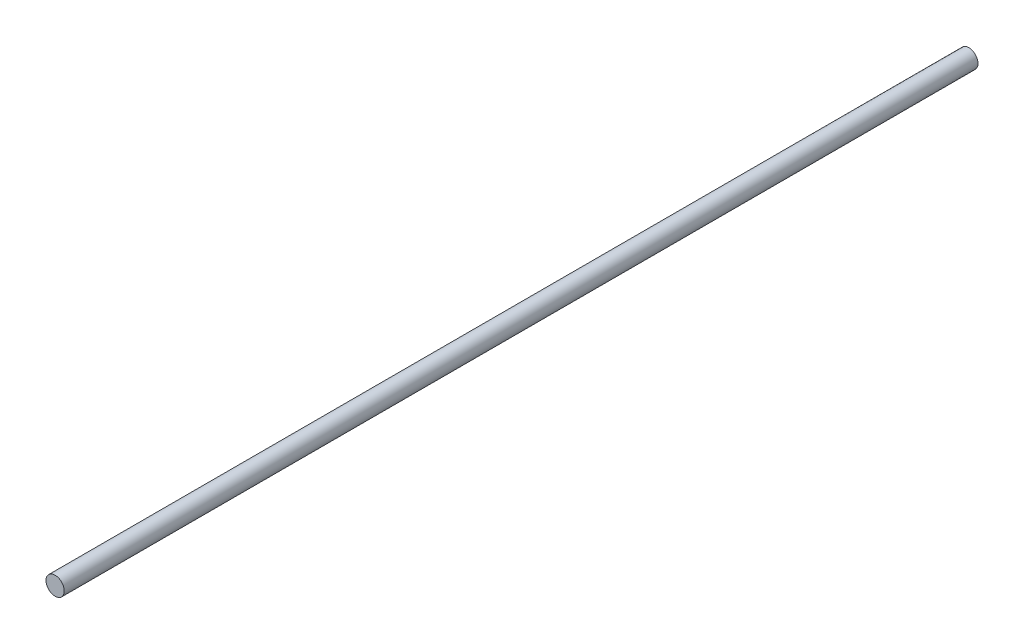
SolidWorks part; units mm, degrees
material "1060 Alloy"
ref_plane "Front Plane" through (0, 0, 0) normal (0, 0, 1) x (1, 0, 0)
ref_plane "Top Plane" through (0, 0, 0) normal (0, 1, 0) x (1, 0, 0)
ref_plane "Right Plane" through (0, 0, 0) normal (1, 0, 0) x (0, 0, -1)
sketch "Sketch1" plane through (0, 0, 0) normal (0, 0, 1) x (1, 0, 0)
  circle A0 centre (0, 0) radius 1
  dimension "D1" = 2
extrude "Boss-Extrude1" add sketch "Sketch1" along normal mid plane 100 contours A0
